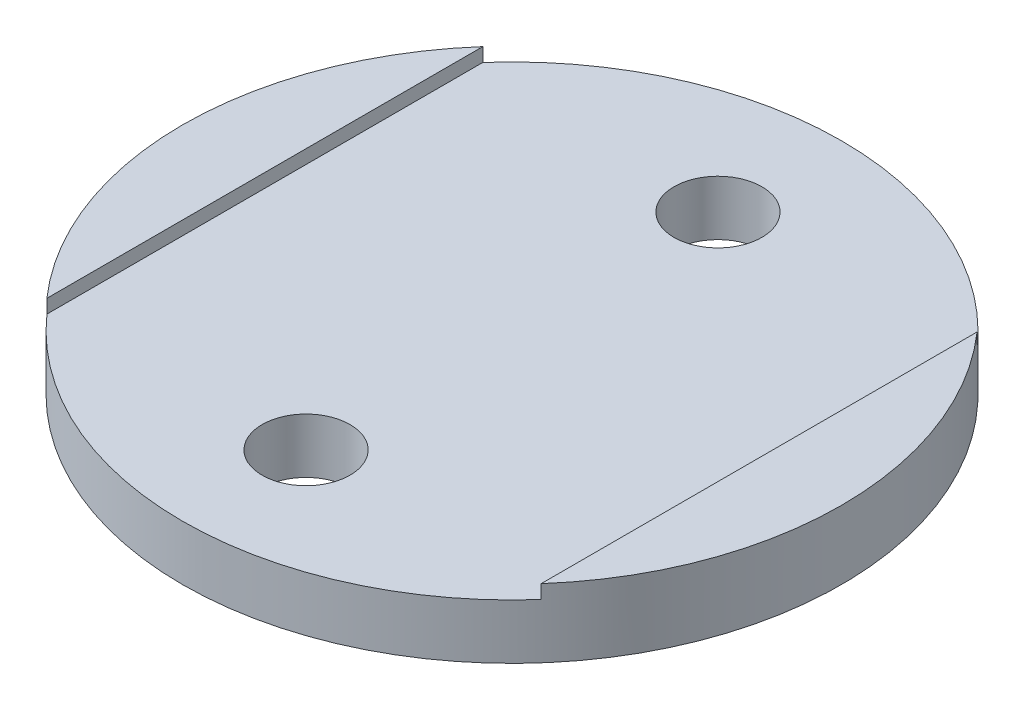
SolidWorks part; units mm, degrees
ref_plane "前视基准面" through (0, 0, 0) normal (0, 0, 1) x (1, 0, 0)
ref_plane "上视基准面" through (0, 0, 0) normal (0, 1, 0) x (1, 0, 0)
ref_plane "右视基准面" through (0, 0, 0) normal (1, 0, 0) x (0, 0, -1)
other "Configuration Table"
sketch "草图1" plane through (0, 0, 0) normal (0, 1, 0) x (1, 0, 0)
  line L0 (0, 0) -> (0, 7.5) construction
  line L1 (0, 0) -> (12, 0) construction
  circle A1 centre (0, 0) radius 12
  circle A2 centre (0, 7.5) radius 1.6
  circle A3 centre (0, -7.5) radius 1.6
  dimension "D1" = 24
  dimension "D2" = 3.2
  dimension "D3" = 7.5
extrude "凸台-拉伸1" add sketch "草图1" along normal blind 2
sketch "草图2" plane through (0, 2, 0) normal (0, 1, 0) x (1, 0, 0)
  line L0 (-9, 7.9373) -> (-9, -7.9373)
  circle A0 centre (0, 0) radius 12 construction
  arc A1 (-9, 7.9373) -> (-9, -7.9373) centre (0, 0) ccw
  dimension "D1" = 9
extrude "凸台-拉伸2" add sketch "草图2" along normal blind 0.5
mirror "镜向2" about plane through (0, 0, 0) normal (1, 0, 0) of "凸台-拉伸2"
